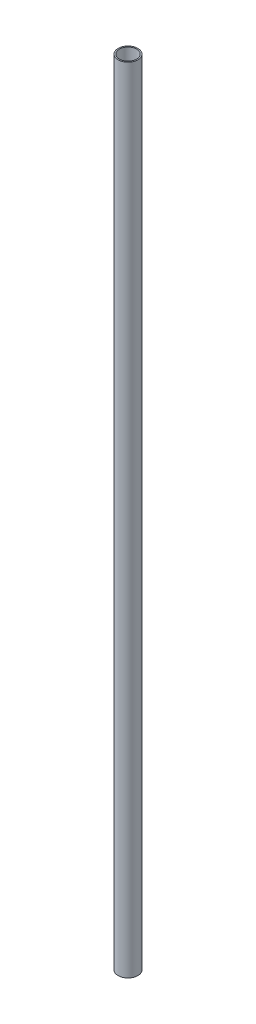
SolidWorks part; units mm, degrees
material "Thornel Mat VMA"
ref_plane "前视基准面" through (0, 0, 0) normal (0, 0, 1) x (1, 0, 0)
ref_plane "上视基准面" through (0, 0, 0) normal (0, 1, 0) x (1, 0, 0)
ref_plane "右视基准面" through (0, 0, 0) normal (1, 0, 0) x (0, 0, -1)
sketch "草图1" plane through (0, 0, 0) normal (0, 1, 0) x (1, 0, 0)
  circle A0 centre (0, 0) radius 8
  circle A1 centre (0, 0) radius 7
  dimension "D1" = 14
  dimension "D2" = 16
extrude "凸台-拉伸1" add sketch "草图1" along normal blind 641
